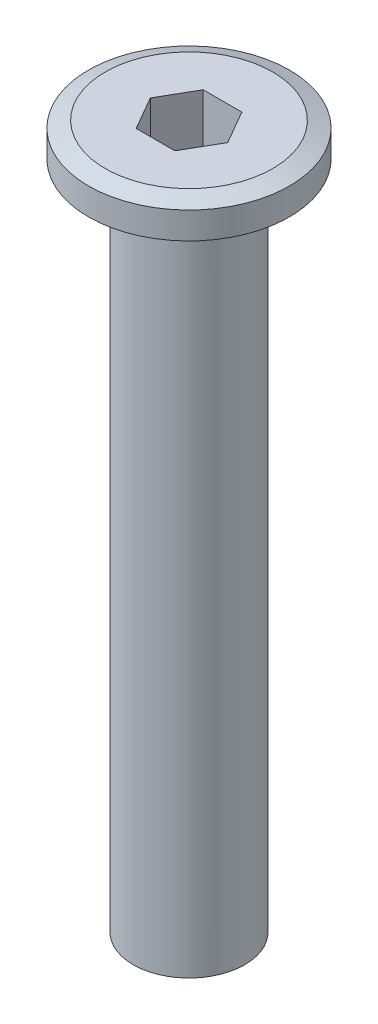
SolidWorks part; units mm, degrees
ref_plane "Front Plane" through (0, 0, 0) normal (0, 0, 1) x (1, 0, 0)
ref_plane "Top Plane" through (0, 0, 0) normal (0, 1, 0) x (1, 0, 0)
ref_plane "Right Plane" through (0, 0, 0) normal (1, 0, 0) x (0, 0, -1)
sketch "Sketch1" plane through (0, 0, 0) normal (0, 0, 1) x (1, 0, 0)
  line L0 (0, 0) -> (0, 1.5)
  line L1 (-2.5, 0) -> (2.5, 0)
  line L5 (-4.5, 0) -> (4.5, 0)
  line L6 (-4.5, 0) -> (-4.5, 1.5)
  line L7 (-4.5, 1.5) -> (4.5, 1.5)
  line L8 (4.5, 0) -> (4.5, 1.5)
  line L9 (-4.5, 1.2) -> (-3.75, 1.5)
  point P1 (0, 0)
  point P8 (0, 1.5)
  dimension "D1" = 3.75
  dimension "D3" = 9
  dimension "D4" = 1.5
  dimension "D6" = 1.2
revolve "Revolve1" add sketch "Sketch1" angle 360 about L0
sketch "Sketch2" plane through (0, 1.5, 0) normal (0, 1, 0) x (1, 0, 0)
  line L1 (1.7321, 0) -> (0.866, 1.5)
  line L2 (0.866, 1.5) -> (-0.866, 1.5)
  line L3 (-0.866, 1.5) -> (-1.7321, 0)
  line L4 (-1.7321, 0) -> (-0.866, -1.5)
  line L5 (-0.866, -1.5) -> (0.866, -1.5)
  line L6 (0.866, -1.5) -> (1.7321, 0)
  circle A0 centre (0, 0) radius 1.5 construction
  dimension "D1" = 3
sketch "Sketch3" plane through (0, 0, 0) normal (0, -1, 0) x (1, 0, 0)
  circle A0 centre (0, 0) radius 2.5
  dimension "D1" = 5
extrude "Boss-Extrude1" add sketch "Sketch3" along normal blind 30
extrude "Cut-Extrude2" cut sketch "Sketch2" against normal blind 3 contours L1 L2 L3 L4 L5 L6
